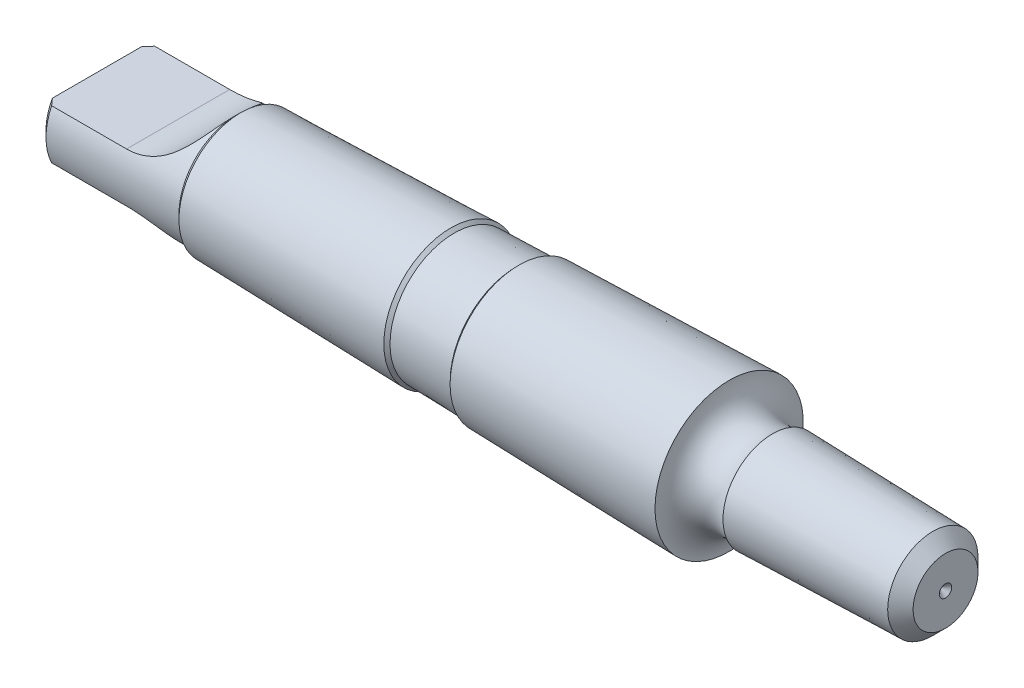
SolidWorks part; units mm, degrees
material "1.0045 (S355JR)"
ref_plane "Plan de face" through (0, 0, 0) normal (0, 0, 1) x (1, 0, 0)
ref_plane "Plan de dessus" through (0, 0, 0) normal (0, 1, 0) x (1, 0, 0)
ref_plane "Plan de droite" through (0, 0, 0) normal (1, 0, 0) x (0, 0, -1)
sketch "Esquisse1" plane through (0, 0, 0) normal (0, 0, 1) x (1, 0, 0)
  line L0 (0, 0) -> (185.401, 0) construction
  line L1 (-102.2516, 9.25) -> (-79.75, 9.25)
  line L2 (-79.75, 9.25) -> (-79, 10)
  line L3 (-79, 10) -> (-44.9982, 10.8608)
  line L4 (-44.9982, 10.8608) -> (-44.4857, 10.3736)
  line L5 (-44.4857, 10.3736) -> (-34.4889, 10.6267)
  line L6 (-34.4889, 10.6267) -> (-34.0018, 11.1392)
  line L7 (-34.0018, 11.1392) -> (0, 12)
  line L8 (0, 12) -> (0, 0) construction
  line L9 (7, 8) -> (35, 7.25)
  line L10 (35, 7.25) -> (35, 1)
  line L11 (35, 1) -> (34, 0)
  line L12 (34, 0) -> (-101.2516, 0)
  line L13 (-101.2516, 0) -> (-102.2516, 1)
  line L14 (-102.2516, 1) -> (-102.2516, 9.25)
  arc A0 (0, 12) -> (7, 8) centre (4.6429, 12) ccw
  dimension "D1" = 18.5
  dimension "D2" = 22.5016
  dimension "D3" = 45
  dimension "D4" = 24
  dimension "D5" = 45
  dimension "D6" = 1
  dimension "D7" = 45
  dimension "D8" = 1
  dimension "D9" = 20
  dimension "D10" = 135
  dimension "D11" = 0.5
  dimension "D12" = 10
  dimension "D13" = 79
  dimension "D14" = 14.5
  dimension "D15" = 16
  dimension "D16" = 35
  dimension "D17" = 28
revolve "Révolution1" add sketch "Esquisse1" angle 360 about L0
chamfer "Chanfrein1" distance 1 angle 45 1 edges at (-102.2516, 0, 9.25)
chamfer "Chanfrein2" distance 2 angle 45 1 edges at (35, 0, 7.25)
sketch "Esquisse2" plane through (0, 0, 0) normal (0, 0, 1) x (1, 0, 0)
  line L0 (-89.1275, 4) -> (-102.2516, 4)
  line L1 (-102.2516, 4) -> (-102.2516, 16)
  line L2 (-102.2516, 16) -> (-78.1275, 16)
  line L3 (-78.1275, 16) -> (-78.1275, 15)
  line L4 (-102.2516, 9.25) -> (-102.2516, -9.25) construction
  line L6 (-102.2516, 0) -> (-116.8582, 0) construction
  arc A0 (-78.1275, 15) -> (-89.1275, 4) centre (-89.1275, 15) cw
  dimension "D1" = 8
  dimension "D3" = 1
  dimension "D2" = 11
extrude "Enlèv. mat.-Extru.1" cut sketch "Esquisse2" against normal mid plane 30
mirror "Symétrie1" about plane through (0, 0, 0) normal (0, 1, 0) of "Enlèv. mat.-Extru.1"
